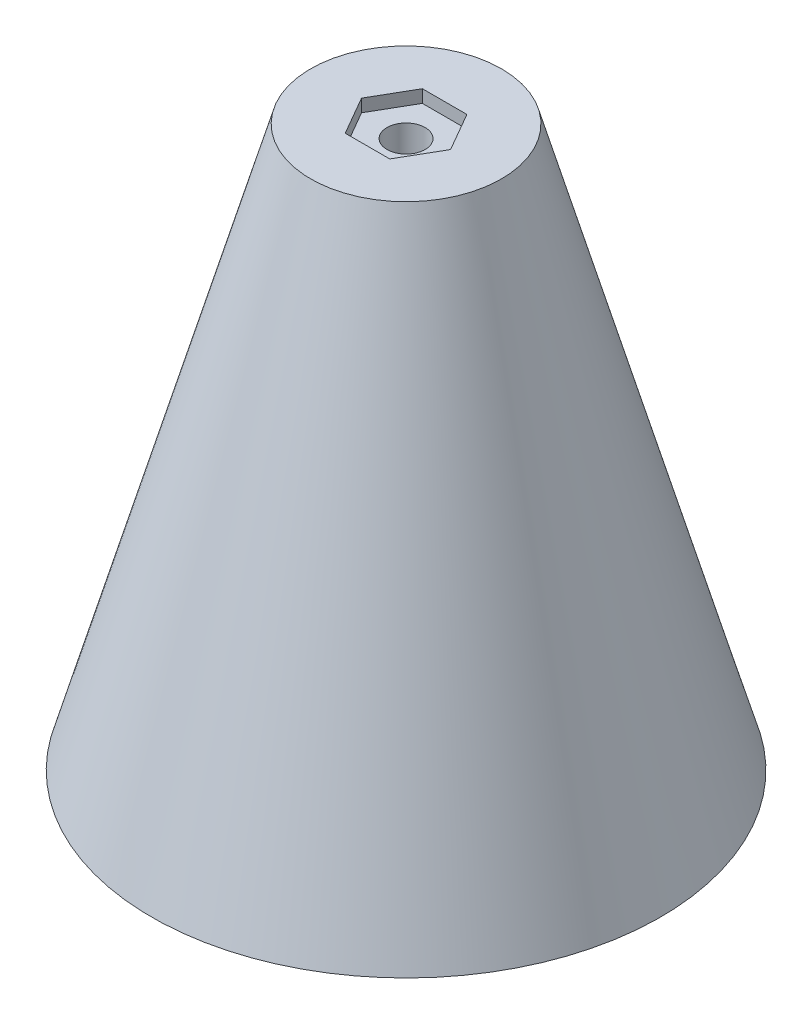
SolidWorks part; units mm, degrees
ref_plane "前视基准面" through (0, 0, 0) normal (0, 0, 1) x (1, 0, 0)
ref_plane "上视基准面" through (0, 0, 0) normal (0, 1, 0) x (1, 0, 0)
ref_plane "右视基准面" through (0, 0, 0) normal (1, 0, 0) x (0, 0, -1)
other "Configuration Table"
sketch "草图3" plane through (0, 0, 0) normal (1, 0, 0) x (0, 0, -1)
  line L0 (-7.5, 0) -> (0, 0)
  line L1 (0, 0) -> (0, -4)
  line L2 (0, -4) -> (-4.6364, -4)
  line L3 (-4.6364, -4) -> (-16, -44)
  line L4 (-16, -44) -> (-20, -44)
  line L5 (-20, -44) -> (-7.5, 0)
  line L6 (0, 28.4507) -> (0, 37.5487) construction
  dimension "D1" = 4
  dimension "D2" = 4
  dimension "D3" = 44
  dimension "D4" = 7.5
  dimension "D5" = 20
revolve "旋转1" add sketch "草图3" angle 360 about L6
sketch "草图4" plane through (0, 0, 0) normal (0, 1, 0) x (1, 0, 0)
  circle A0 centre (0, 0) radius 1.5
extrude "切除-拉伸1" cut sketch "草图4" against normal blind 10 contours A0
chamfer "倒角1" distance 0.5 angle 45 1 edges at (0, -4, 1.5)
sketch "草图5" plane through (0, 0, 0) normal (0, 1, 0) x (1, 0, 0)
  line L1 (3.5, 0) -> (1.75, 3.0311)
  line L2 (1.75, 3.0311) -> (-1.75, 3.0311)
  line L3 (-1.75, 3.0311) -> (-3.5, 0)
  line L4 (-3.5, 0) -> (-1.75, -3.0311)
  line L5 (-1.75, -3.0311) -> (1.75, -3.0311)
  line L6 (1.75, -3.0311) -> (3.5, 0)
  circle A0 centre (0, 0) radius 3.0311 construction
  dimension "D1" = 3.5
extrude "切除-拉伸2" cut sketch "草图5" against normal blind 1
